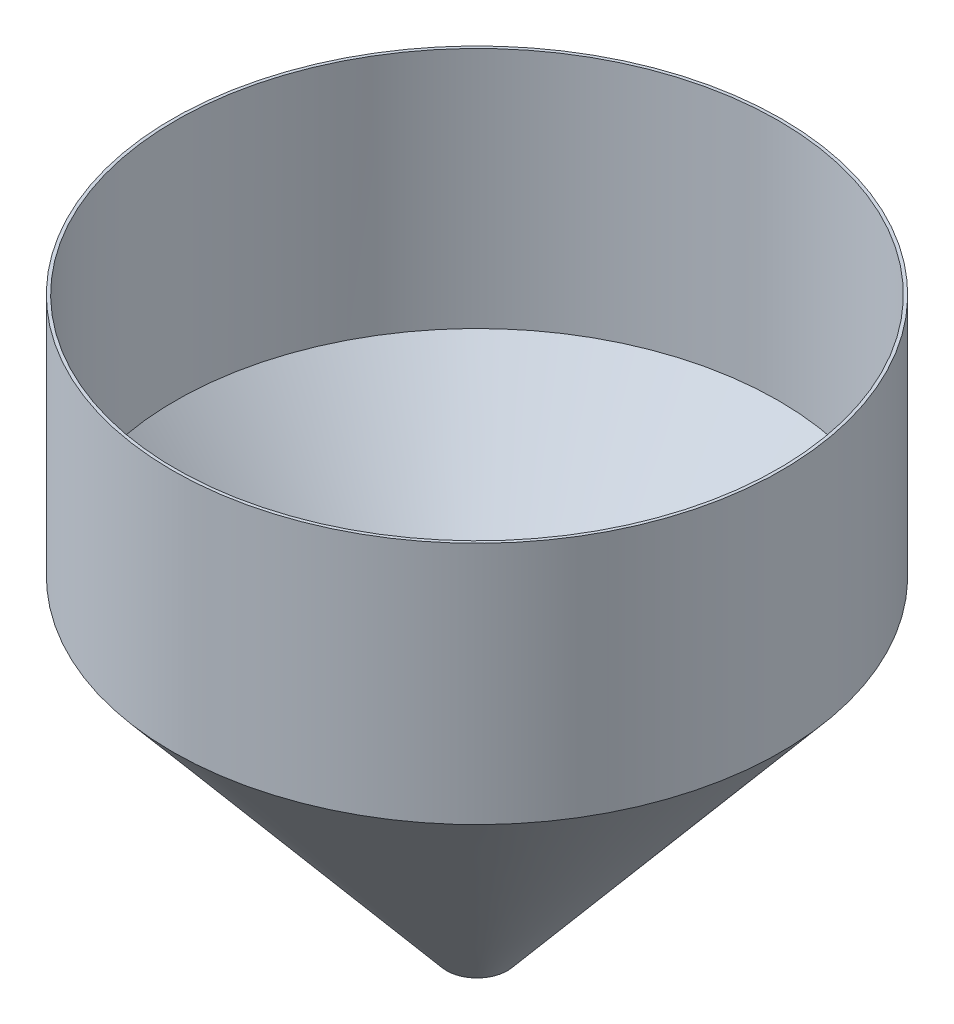
SolidWorks part; units mm, degrees
ref_plane "Front Plane" through (0, 0, 0) normal (0, 0, 1) x (1, 0, 0)
ref_plane "Top Plane" through (0, 0, 0) normal (0, 1, 0) x (1, 0, 0)
ref_plane "Right Plane" through (0, 0, 0) normal (1, 0, 0) x (0, 0, -1)
sketch "Sketch1" plane through (0, 0, 0) normal (0, 0, 1) x (1, 0, 0)
  line L0 (-100, 187.2578) -> (-100, 107.2578)
  line L1 (-100, 107.2578) -> (-10, 0)
  line L2 (0, 0) -> (0, 187.2578) construction
  line L3 (-100, 187.2578) -> (0, 187.2578)
  line L4 (0, 187.2578) -> (0, 0)
  line L5 (0, 0) -> (-10, 0)
  point P2 (-1.1738, -7.4648)
  point P7 (0, 13.1783)
  point P9 (0, 17.9661)
  point P10 (0, -0.1829)
  point P11 (0, 0)
  point P12 (0, 16.7676)
  dimension "D1" = 100
  dimension "D2" = 50
  dimension "D3" = 80
  dimension "D4" = 10
revolve "Revolve1" add sketch "Sketch1" angle 360 about L2
shell "Shell1" thickness 1
